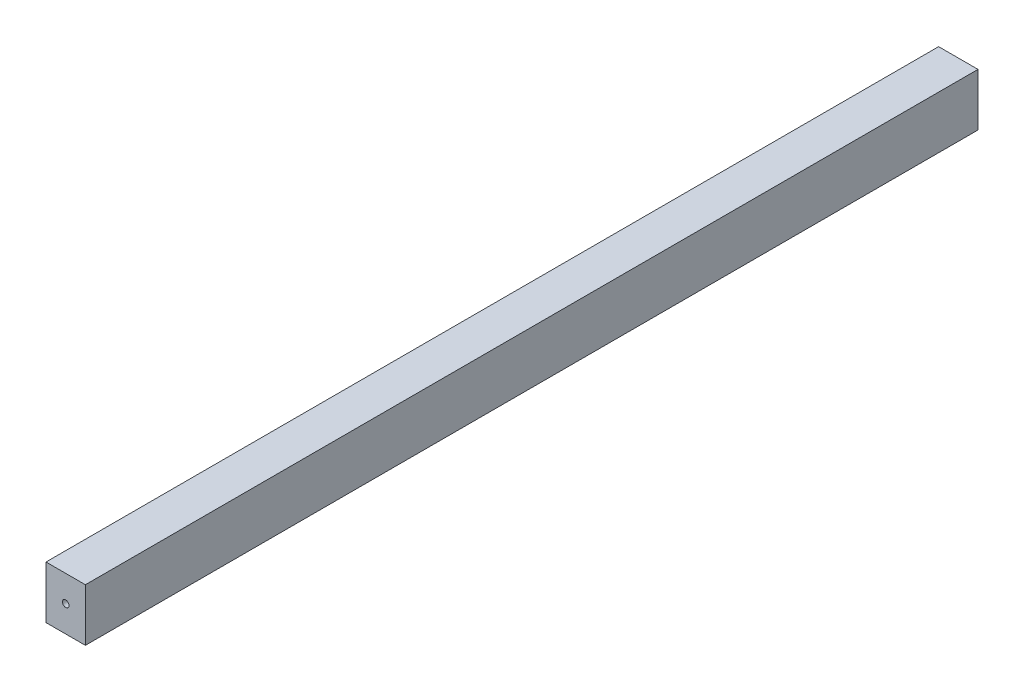
SolidWorks part; units mm, degrees
ref_plane "Front Plane" through (0, 0, 0) normal (0, 0, 1) x (1, 0, 0)
ref_plane "Top Plane" through (0, 0, 0) normal (0, 1, 0) x (1, 0, 0)
ref_plane "Right Plane" through (0, 0, 0) normal (1, 0, 0) x (0, 0, -1)
sketch "Sketch1" plane through (0, 0, 0) normal (0, 0, 1) x (1, 0, 0)
  line L0 (19.05, 50.8) -> (19.05, 0) construction
  line L1 (0, 0) -> (38.1, 0)
  line L2 (0, 0) -> (0, 50.8)
  line L3 (0, 50.8) -> (38.1, 50.8)
  line L4 (38.1, 0) -> (38.1, 50.8)
  circle A0 centre (19.05, 25.4) radius 3.175
  dimension "D1" = 50.8
  dimension "D2" = 38.1
extrude "Boss-Extrude1" add sketch "Sketch1" along normal blind 863.6
